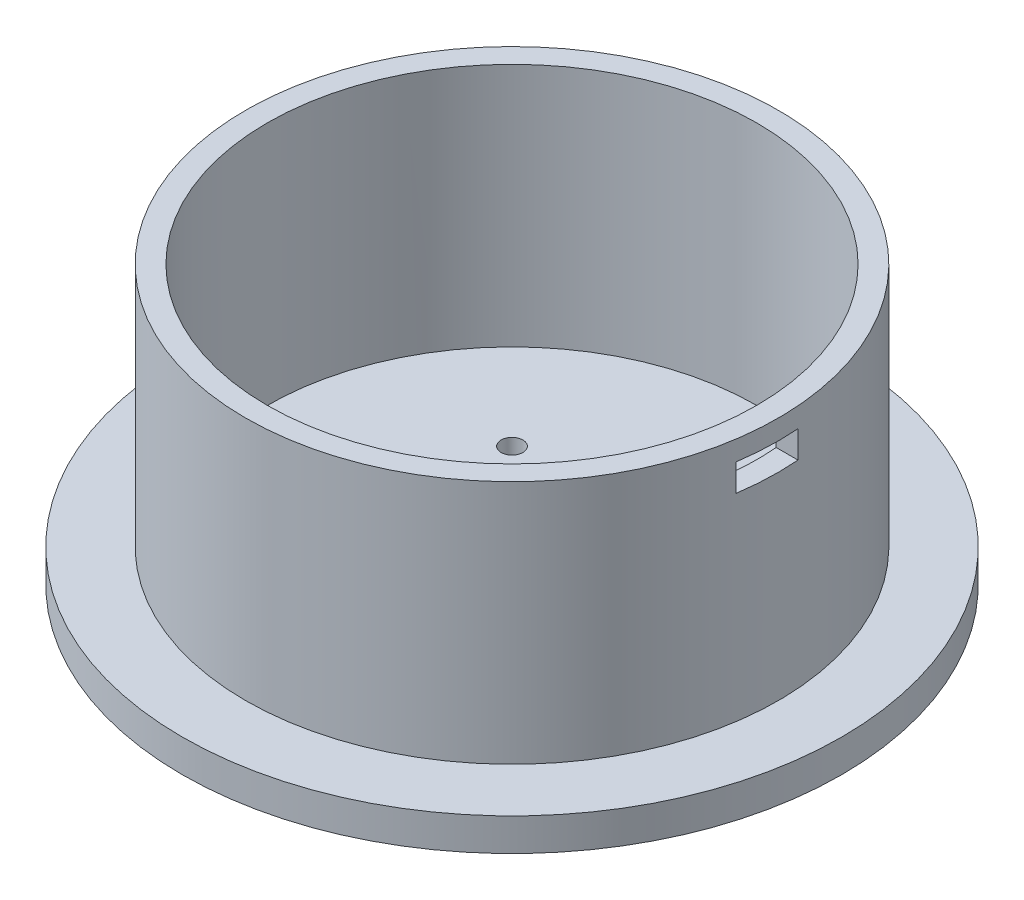
SolidWorks part; units mm, degrees
ref_plane "Front Plane" through (0, 0, 0) normal (0, 0, 1) x (1, 0, 0)
ref_plane "Top Plane" through (0, 0, 0) normal (0, 1, 0) x (1, 0, 0)
ref_plane "Right Plane" through (0, 0, 0) normal (1, 0, 0) x (0, 0, -1)
sketch "Sketch1" plane through (0, 0, 0) normal (0, 1, 0) x (1, 0, 0)
  circle A0 centre (-5.2333, 2.2753) radius 45
  circle A1 centre (-5.2333, 2.2753) radius 60.625
  dimension "D1" = 90
  dimension "D2" = 121.25
extrude "Boss-Extrude1" add sketch "Sketch1" along normal blind 4
sketch "Sketch2" plane through (0, 4, 0) normal (0, 1, 0) x (1, 0, 0)
  circle A0 centre (-5.2333, 2.2753) radius 45
  circle A1 centre (-5.2333, 2.2753) radius 49
  dimension "D1" = 98
extrude "Boss-Extrude2" add sketch "Sketch2" along normal blind 45
sketch "Sketch3" plane through (0, 0, 0) normal (0, -1, 0) x (-1, 0, 0)
  circle A0 centre (5.2333, 2.2753) radius 45
extrude "Boss-Extrude3" add sketch "Sketch3" against normal blind 4
sketch "Sketch4" plane through (0, 0, 0) normal (0, -1, 0) x (1, 0, 0)
  line L0 (-56.2787, 21.9495) -> (-47.2445, 17.6621)
  line L1 (-47.2445, 17.6621) -> (-56.2787, 21.9495)
  circle A0 centre (-5.2333, -2.2753) radius 46.502
  circle A1 centre (-5.2333, -2.2753) radius 56.502
  dimension "D1" = 10
extrude "Boss-Extrude7" add sketch "Sketch4" along normal blind 2 contours L1 A1 | A0
sketch "Sketch5" plane through (0, -2, 0) normal (0, -1, 0) x (-1, 0, 0)
  line L0 (5.2333, 2.2753) -> (5.2333, -13.7247)
  line L1 (5.2333, -13.7247) -> (5.2333, 2.2753)
  line L2 (5.2333, -13.7247) -> (-10.7667, -13.7247)
  line L3 (-10.7667, -13.7247) -> (5.2333, -13.7247)
  line L4 (5.2333, -13.7247) -> (21.2333, -13.7247)
  line L5 (21.2333, -13.7247) -> (5.2333, -13.7247)
  line L6 (5.2333, 2.2753) -> (5.2333, 18.2753)
  line L7 (5.2333, 18.2753) -> (5.2333, 2.2753)
  line L8 (5.2333, 18.2753) -> (-10.7667, 18.2753)
  line L9 (-10.7667, 18.2753) -> (5.2333, 18.2753)
  line L10 (5.2333, 18.2753) -> (21.2333, 18.2753)
  line L11 (21.2333, 18.2753) -> (5.2333, 18.2753)
  circle A0 centre (5.2333, 2.2753) radius 2.5
  circle A1 centre (-10.7667, -13.7247) radius 2
  circle A2 centre (21.2333, -13.7247) radius 2
  circle A3 centre (21.2333, 18.2753) radius 2
  circle A4 centre (-10.7667, 18.2753) radius 2
  dimension "D1" = 5
  dimension "D4" = 4
  dimension "D6" = 4
  dimension "D10" = 4
  dimension "D11" = 4
  dimension "D2" = 16
  dimension "D3" = 16
  dimension "D5" = 16
  dimension "D7" = 16
  dimension "D8" = 16
  dimension "D9" = 16
extrude "Cut-Extrude1" cut sketch "Sketch5" against normal blind 10 contours A3 | A4 | A1 | A2 | A0
ref_plane "Plane1" through (43.7667, 0, 0) normal (1, 0, 0) x (0, 0, -1)
sketch "Sketch6" plane through (43.7667, 0, 0) normal (1, 0, 0) x (0, 0, -1)
  line L1 (-4.9957, 45.3584) -> (6.0043, 45.3584)
  line L2 (-4.9957, 45.3584) -> (-4.9957, 40.3584)
  line L3 (-4.9957, 40.3584) -> (6.0043, 40.3584)
  line L4 (6.0043, 45.3584) -> (6.0043, 40.3584)
  dimension "D1" = 11
  dimension "D2" = 5
extrude "Cut-Extrude2" cut sketch "Sketch6" against normal blind 10 contours L2 L1 L4 L3
